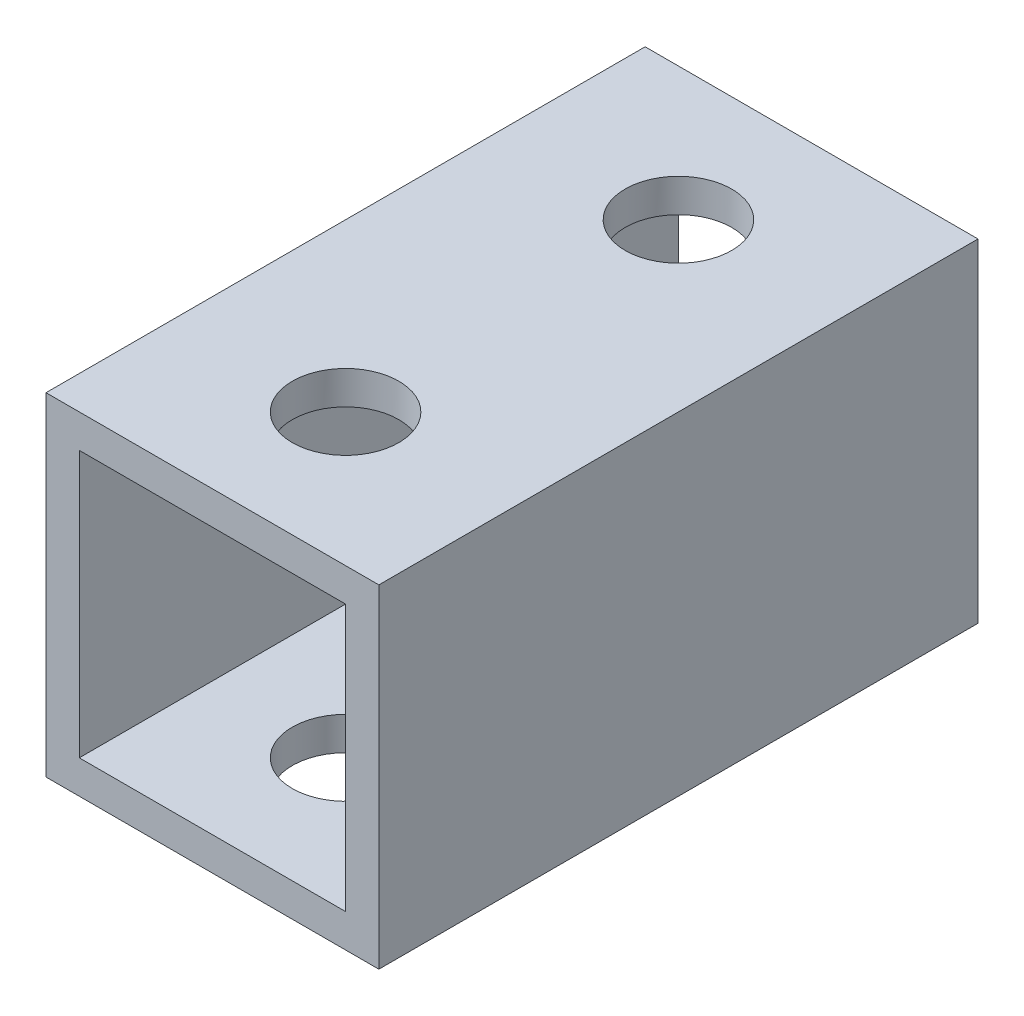
SolidWorks part; units mm, degrees
material "6061 合金"
ref_plane "正面" through (0, 0, 0) normal (0, 0, 1) x (1, 0, 0)
ref_plane "平面" through (0, 0, 0) normal (0, 1, 0) x (1, 0, 0)
ref_plane "右側面" through (0, 0, 0) normal (1, 0, 0) x (0, 0, -1)
sketch "断面 スケッチ" plane through (0, 0, 0) normal (0, 0, 1) x (1, 0, 0)
  line L1 (-5, -5) -> (5, -5)
  line L2 (-5, -5) -> (-5, 5)
  line L3 (-5, 5) -> (5, 5)
  line L4 (5, -5) -> (5, 5)
  line L5 (-5, -5) -> (5, 5) construction
  line L6 (-5, 5) -> (5, -5) construction
  point P0 (0, 0)
  dimension "D1" = 10
extrude "フレーム全長" add sketch "断面 スケッチ" along normal blind 18 thin thin type one direction reverse wall 1
sketch "上面穴 スケッチ" plane through (0, 5, 0) normal (0, 1, 0) x (1, 0, 0)
  line L0 (0, 0) -> (0, -18) construction
  line L1 (5, 0) -> (-5, 0) construction
  line L2 (5, -18) -> (-5, -18) construction
  line L3 (-5, -9) -> (5, -9) construction
  line L4 (-5, -18) -> (-5, 0) construction
  line L5 (5, -18) -> (5, 0) construction
  circle A0 centre (0, -4) radius 1.6
  circle A1 centre (0, -14) radius 1.6
  dimension "D1" = 4
  dimension "D2" = 3.2
  dimension "D3" = 10
sketch "側面穴 スケッチ" plane through (5, 0, 0) normal (1, 0, 0) x (0, 0, -1)
  line L0 (0, 0) -> (-18, 0) construction
  line L1 (0, -5) -> (0, 5) construction
  line L2 (-18, -5) -> (-18, 5) construction
  line L3 (-9, 5) -> (-9, -5) construction
  line L4 (-18, 5) -> (0, 5) construction
  line L5 (-18, -5) -> (0, -5) construction
  circle A0 centre (-15, 0) radius 1.6
  dimension "D1" = 15
  dimension "D2" = 3.2
extrude "上面穴貫通" cut sketch "上面穴 スケッチ" against normal through all
extrude "側面穴貫通" [suppressed] cut sketch "側面穴 スケッチ" against normal through all
fillet "フィレット" [suppressed] radius 5
